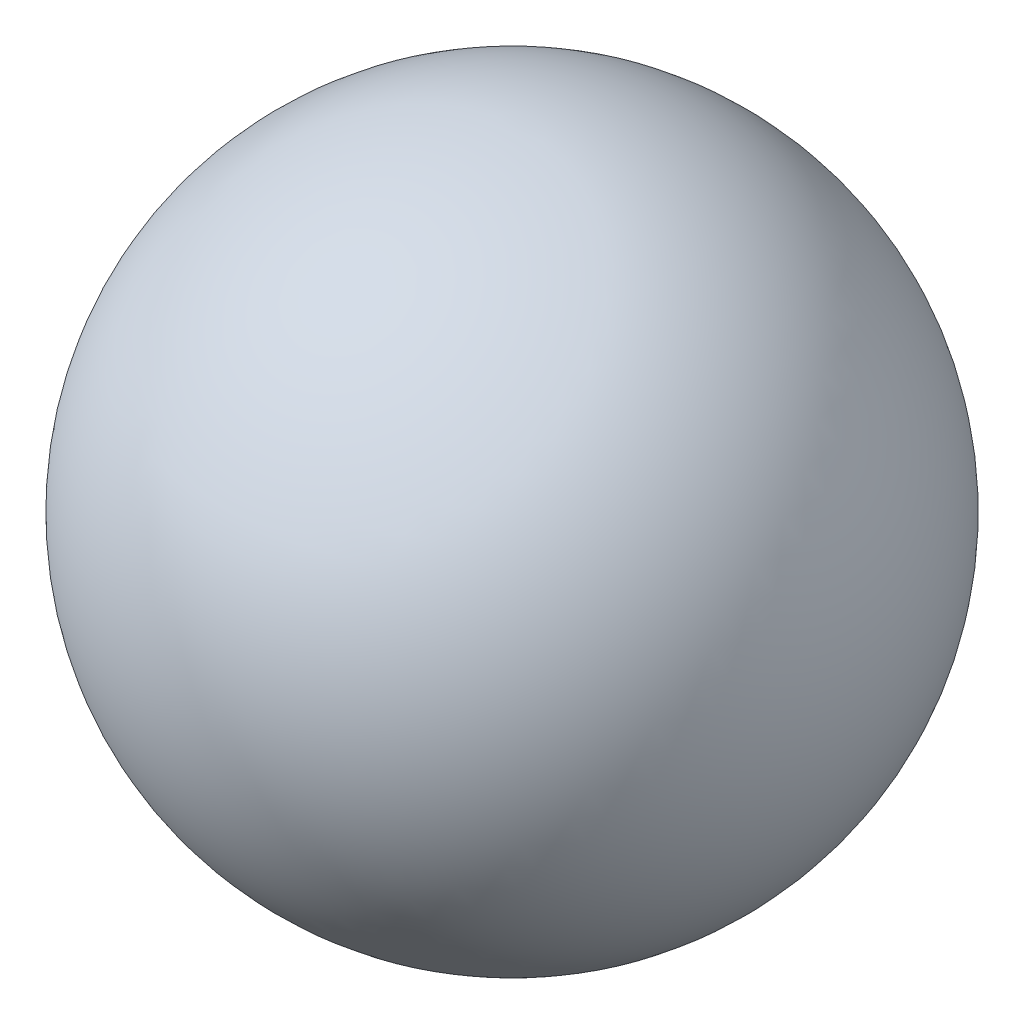
SolidWorks part; units mm, degrees
ref_plane "Front Plane" through (0, 0, 0) normal (0, 0, 1) x (1, 0, 0)
ref_plane "Top Plane" through (0, 0, 0) normal (0, 1, 0) x (1, 0, 0)
ref_plane "Right Plane" through (0, 0, 0) normal (1, 0, 0) x (0, 0, -1)
sketch "Sketch1" plane through (0, 0, 0) normal (0, 0, 1) x (1, 0, 0)
  line L0 (0, 105.0842) -> (0, -101.9811) construction
  line L1 (0, 33.5) -> (0, 28.75)
  line L2 (0, -28.75) -> (0, -33.5)
  arc A0 (0, 33.5) -> (0, -33.5) centre (0, 0) ccw
  arc A1 (0, 28.75) -> (0, -28.75) centre (0, 0) ccw
  dimension "D1" = 33.5
  dimension "D2" = 4.75
revolve "Revolve1" add sketch "Sketch1" angle 360 about L0
